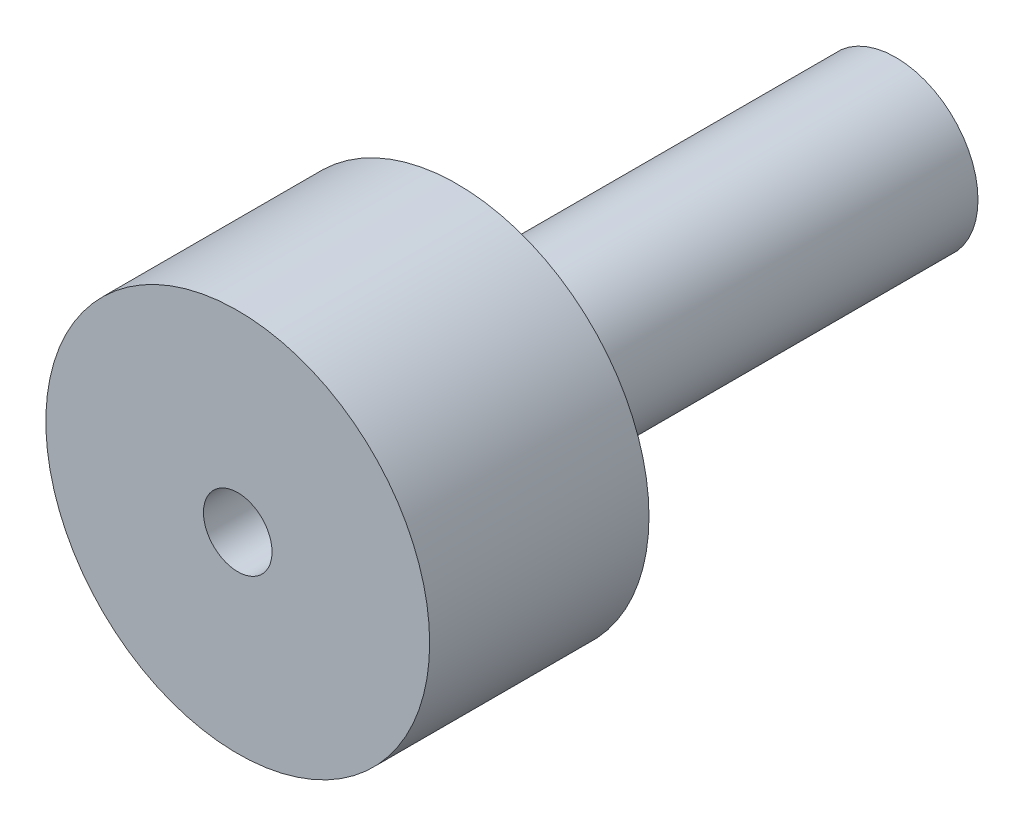
SolidWorks part; units mm, degrees
ref_plane "前视基准面" through (0, 0, 0) normal (0, 0, 1) x (1, 0, 0)
ref_plane "上视基准面" through (0, 0, 0) normal (0, 1, 0) x (1, 0, 0)
ref_plane "右视基准面" through (0, 0, 0) normal (1, 0, 0) x (0, 0, -1)
other "Configuration Table"
sketch "草图1" plane through (0, 0, 0) normal (0, 0, 1) x (1, 0, 0)
  circle A0 centre (0, 0) radius 2.5
  circle A1 centre (0, 0) radius 14
  dimension "D1" = 28
  dimension "D2" = 5
extrude "凸台-拉伸1" add sketch "草图1" along normal blind 16
sketch "草图2" plane through (0, 0, 0) normal (0, 0, -1) x (-1, 0, 0)
  circle A0 centre (0, 0) radius 6
  dimension "D1" = 12
extrude "凸台-拉伸2" add sketch "草图2" along normal blind 32
sketch "草图3" plane through (0, 0, 0) normal (0, 0, 1) x (1, 0, 0)
  circle A1 centre (0, 0) radius 2.5
  circle A2 centre (0, 0) radius 2.5
  dimension "D1" = 0
extrude "切除-拉伸1" cut sketch "草图3" against normal up to next
